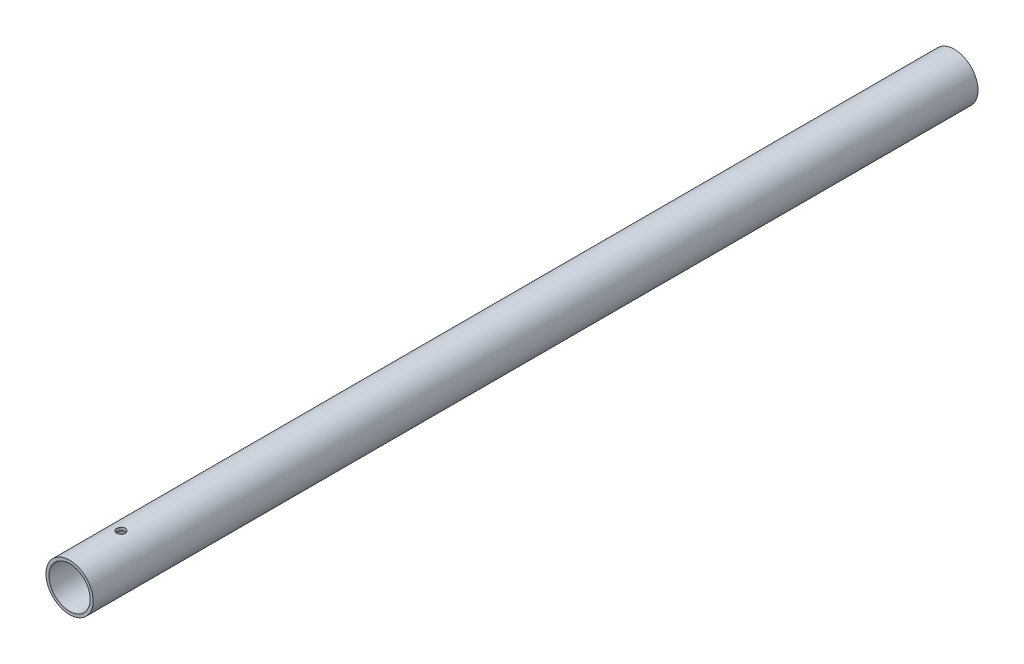
SolidWorks part; units mm, degrees
material "Thornel Mat VMA"
ref_plane "Front Plane" through (0, 0, 0) normal (0, 0, 1) x (1, 0, 0)
ref_plane "Top Plane" through (0, 0, 0) normal (0, 1, 0) x (1, 0, 0)
ref_plane "Right Plane" through (0, 0, 0) normal (1, 0, 0) x (0, 0, -1)
sketch "Sketch1" plane through (0, 0, 0) normal (0, 0, 1) x (1, 0, 0)
  circle A0 centre (0, 0) radius 7
  circle A1 centre (0, 0) radius 8
  dimension "D1" = 16
  dimension "D2" = 14
extrude "Boss-Extrude1" add sketch "Sketch1" along normal blind 300
ref_plane "Plane1" through (0, 8, 0) normal (0, 1, 0) x (1, 0, 0)
hole_wizard "M2.5 Clearance Hole1" positions "Sketch4" profile "Sketch5" hole size "M2.5" standard "ANSI Metric" end condition through all
sketch "Sketch4" plane through (0, 8, 0) normal (0, 1, 0) x (1, 0, 0)
  line L0 (-8, -300) -> (8, -300) construction
  point P0 (0, -282.6)
  point P5 (0, 0)
  dimension "D1" = 17.4
sketch "Sketch5" plane through (0, 8, 282.6) normal (1, 0, 0) x (0, 0, 1)
  line L0 (0, 0) -> (0, 16)
  line L1 (0, 16) -> (1.45, 16)
  line L2 (1.45, 16) -> (1.45, 0)
  line L5 (1.45, 0) -> (0, 0)
  line L11 (0, -6.35) -> (0, 107.95) construction
  dimension "Thru Hole Dia." = 2.9
  dimension "Thru Hole Depth" = 16
